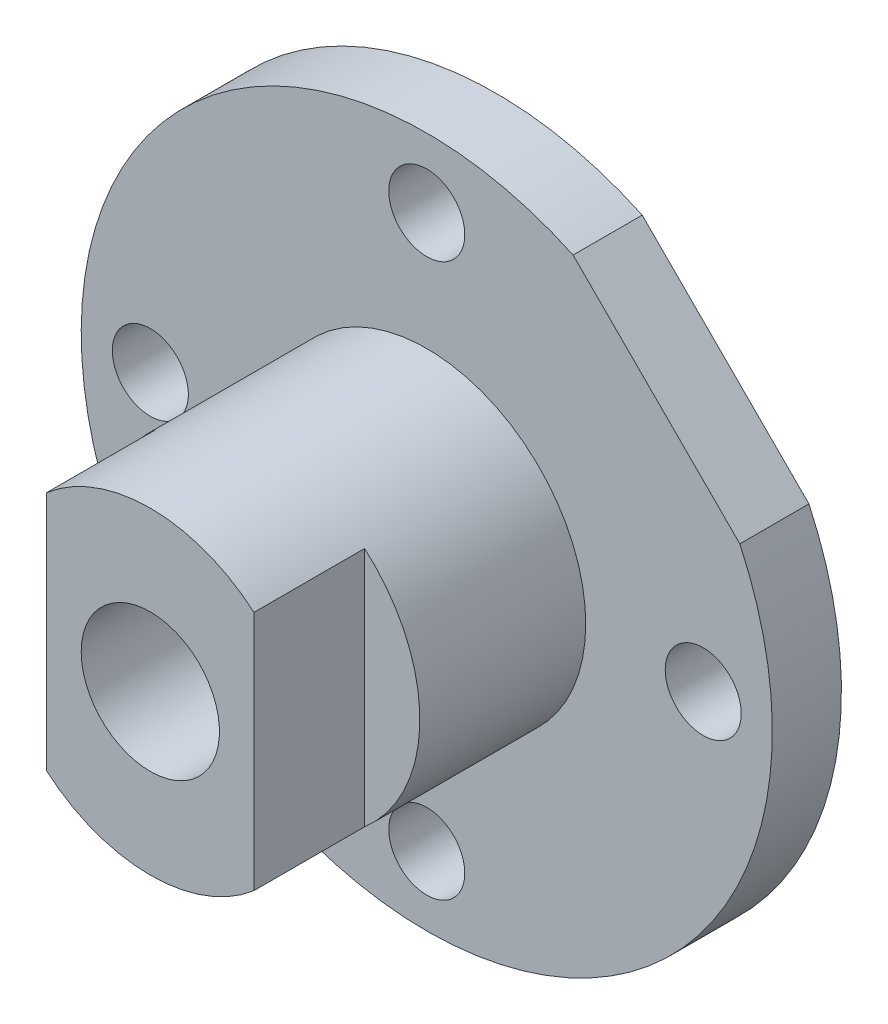
SolidWorks part; units mm, degrees
ref_plane "Front Plane" through (0, 0, 0) normal (0, 0, 1) x (1, 0, 0)
ref_plane "Top Plane" through (0, 0, 0) normal (0, 1, 0) x (1, 0, 0)
ref_plane "Right Plane" through (0, 0, 0) normal (1, 0, 0) x (0, 0, -1)
sketch "Sketch1" plane through (0, 0, 0) normal (0, 0, 1) x (1, 0, 0)
  circle A0 centre (0, 0) radius 11.5
  dimension "D1" = 23
extrude "Boss-Extrude1" add sketch "Sketch1" along normal blind 25
sketch "Sketch2" plane through (0, 0, 0) normal (0, 0, -1) x (-1, 0, 0)
  circle A0 centre (0, 0) radius 25
  dimension "D1" = 50
extrude "Boss-Extrude2" add sketch "Sketch2" against normal blind 5
sketch "Sketch3" plane through (0, 0, 0) normal (0, 0, -1) x (-1, 0, 0)
  circle A0 centre (0, 0) radius 5
  dimension "D1" = 10
extrude "Cut-Extrude1" cut sketch "Sketch3" against normal through all
sketch "Sketch4" plane through (0, 0, 0) normal (0, 0, -1) x (-1, 0, 0)
  line L1 (8, 0) -> (4, 6.9282)
  line L2 (4, 6.9282) -> (-4, 6.9282)
  line L3 (-4, 6.9282) -> (-8, 0)
  line L4 (-8, 0) -> (-4, -6.9282)
  line L5 (-4, -6.9282) -> (4, -6.9282)
  line L6 (4, -6.9282) -> (8, 0)
  circle A0 centre (0, 0) radius 6.9282 construction
  dimension "D1" = 16
extrude "Cut-Extrude2" cut sketch "Sketch4" against normal blind 10
sketch "Sketch5" plane through (0, 0, 0) normal (0, 1, 0) x (1, 0, 0)
  line L1 (11.5, -25) -> (7.5, -25)
  line L2 (11.5, -25) -> (11.5, -17)
  line L3 (11.5, -17) -> (7.5, -17)
  line L4 (7.5, -25) -> (7.5, -17)
  dimension "D1" = 7.5
  dimension "D2" = 8
extrude "Cut-Extrude3" cut sketch "Sketch5" against normal through all and the other way through all
mirror "Mirror1" about plane through (0, 0, 0) normal (1, 0, 0) of "Cut-Extrude3"
hole_wizard "M5 Clearance Hole1" positions "Sketch7" profile "Sketch6" hole size "M5" standard "ANSI Metric" end condition through all
sketch "Sketch7" plane through (0, 0, 0) normal (0, 0, -1) x (-1, 0, 0)
  circle A0 centre (0, 0) radius 20 construction
  point P0 (0, 20)
  point P13 (-20, 0)
  point P15 (20, 0)
  point P17 (0, -20)
  dimension "D1" = 40
sketch "Sketch6" plane through (0, 20, 0) normal (1, 0, 0) x (0, 1, 0)
  line L0 (0, 0) -> (0, 25)
  line L1 (0, 25) -> (2.75, 25)
  line L2 (2.75, 25) -> (2.75, 0)
  line L5 (2.75, 0) -> (0, 0)
  line L11 (0, -6.35) -> (0, 107.95) construction
  dimension "Thru Hole Dia." = 5.5
  dimension "Thru Hole Depth" = 25
sketch "Sketch8" plane through (0, 0, 0) normal (0, 0, -1) x (-1, 0, 0)
  line L0 (-22.6482, 10.5858) -> (-10.5858, 22.6482)
  line L1 (0, 0) -> (-16.617, 16.617) construction
  line L2 (0, 0) -> (0, 25) construction
  circle A0 centre (0, 0) radius 25 construction
  arc A1 (-10.5858, 22.6482) -> (-22.6482, 10.5858) centre (0, 0) ccw
  dimension "D1" = 45
  dimension "D2" = 23.5
extrude "Cut-Extrude4" cut sketch "Sketch8" against normal through all
sketch "Sketch9" plane through (0, 0, 10) normal (0, 0, -1) x (-1, 0, 0)
  circle A0 centre (0, 0) radius 5 construction
  circle A1 centre (0, 0) radius 5
extrude "PRINT CAP" [suppressed] add sketch "Sketch9" against normal blind 0.2
